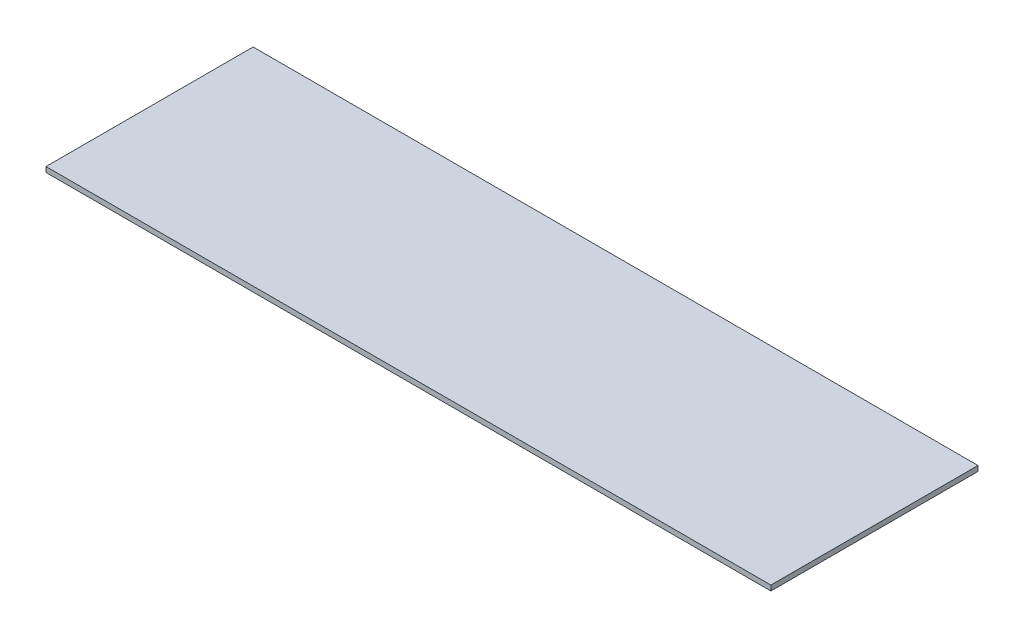
SolidWorks part; units mm, degrees
ref_plane "Front Plane" through (0, 0, 0) normal (0, 0, 1) x (1, 0, 0)
ref_plane "Top Plane" through (0, 0, 0) normal (0, 1, 0) x (1, 0, 0)
ref_plane "Right Plane" through (0, 0, 0) normal (1, 0, 0) x (0, 0, -1)
sketch "Sketch1" plane through (0, 0, 0) normal (0, 1, 0) x (1, 0, 0)
  line L0 (-70, -3.5) -> (70, -3.5) construction
  line L1 (-70, -20) -> (70, -20)
  line L2 (-70, -20) -> (-70, 20)
  line L3 (-70, 20) -> (70, 20)
  line L4 (70, -20) -> (70, 20)
  line L5 (-70, -20) -> (70, 20) construction
  line L6 (-70, 20) -> (70, -20) construction
  text T0 "<b>26-27-00012863</b>\r\n"
  point P0 (0, 0)
  dimension "D1" = 40
  dimension "D2" = 140
  dimension "D3" = 16.5
extrude "Boss-Extrude1" add sketch "Sketch1" along normal blind 1 contours L1 L4 L3 L2
